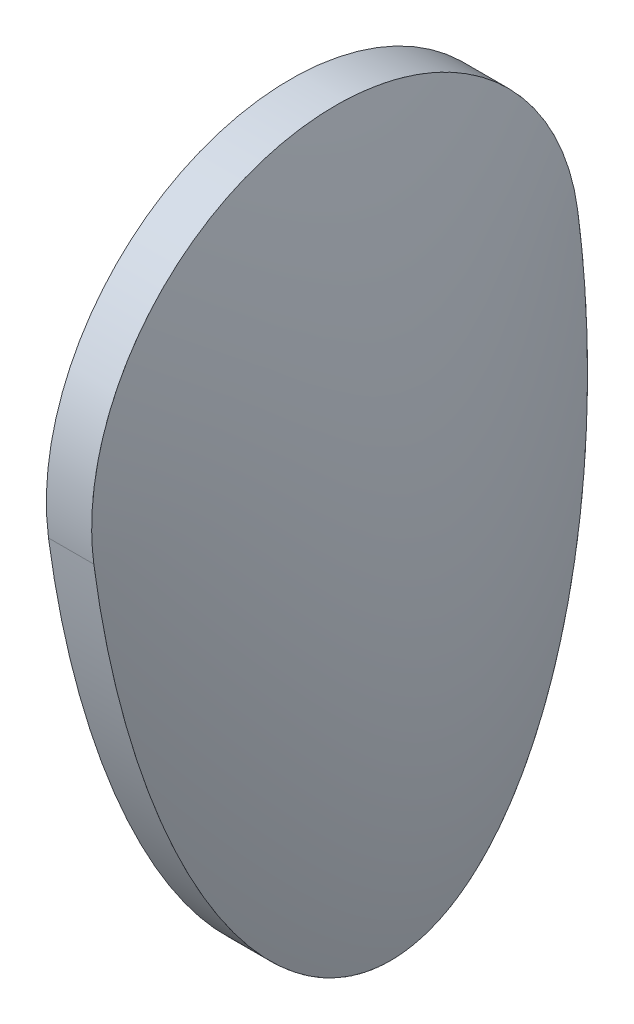
SolidWorks part; units mm, degrees
ref_plane "Plano frontal" through (0, 0, 0) normal (0, 0, 1) x (1, 0, 0)
ref_plane "Plano superior" through (0, 0, 0) normal (0, 1, 0) x (1, 0, 0)
ref_plane "Plano direito" through (0, 0, 0) normal (1, 0, 0) x (0, 0, -1)
sketch "Esboço43" plane through (0, 0, 0) normal (1, 0, 0) x (0, 0, -1)
  line L0 (0, 0) -> (0, -150) construction
  line L1 (0, -150) -> (20, -150) construction
  arc A0 (69.386, 9.2515) -> (-69.386, -9.2515) centre (0, 0) ccw
  ellipse E0 centre (0, 0) end of major axis (20, -150) minor radius 70 (-69.386, -9.2515) -> (69.386, 9.2515) ccw
  dimension "D1" = 140
  dimension "D2" = 150
  dimension "D3" = 20
extrude "Ressalto-extrusão11" add sketch "Esboço43" along normal blind 13
sketch3d "3DSketch4"
  arc A0 (13, 69.3586, 9.4543) -> (13, -149.9687, -20.2284) centre (-399.0364, -36.5209, -33.3487) cw
  arc A1 (13, 9.2515, -69.386) -> (13, -9.2515, 69.386) centre (13, 0, 0) ccw construction
  spline S0 degree 3 poles (13, -9.2515, 69.386) (13, -309.2515, 29.386) (13, -290.7485, -109.386) (13, 9.2515, -69.386) knots 0 0 0 0 1 1 1 1 weights 1 0.333333 0.333333 1 construction
  point P2 (-369.8245, 20.6877, -456.0665)
  point P8 (83, 0, 0)
surface "Superfície-Preenchimento3"
sketch "Esboço44" plane through (0, 0, 0) normal (1, 0, 0) x (0, 0, -1)
  line L0 (0, 70) -> (-25.8959, 70) construction
  circle A2 centre (-5, 28) radius 20
  spline S0 degree 3 poles (69.386, 9.2515) (69.3402, 9.5842) (69.2487, 10.2496) (69.0931, 11.2451) (68.9244, 12.2383) (68.741, 13.229) (68.5435, 14.217) (68.2109, 15.7648) (67.7009, 17.863) (66.9516, 20.4934) (65.8165, 23.9584) (64.1451, 28.2026) (62.1475, 32.3034) (59.9151, 36.2766) (56.9602, 40.8822) (53.5638, 45.1853) (49.234, 49.868) (45.2095, 53.5903) (40.8489, 56.8962) (37.0624, 59.4323) (33.1303, 61.7444) (29.0296, 63.7424) (24.8229, 65.4953) (20.5169, 67.0003) (16.1064, 68.1645) (11.6395, 69.0676) (7.1232, 69.7083) (2.5707, 69.9943) (-1.9867, 70.0133) (-7.4506, 69.7159) (-12.869, 68.8853) (-18.1923, 67.6377) (-22.565, 66.3386) (-26.8228, 64.7021) (-30.9737, 62.8208) (-35.011, 60.6977) (-38.8702, 58.266) (-42.5771, 55.6148) (-46.1256, 52.7486) (-49.4394, 49.6141) (-52.5613, 46.2939) (-56.0701, 42.0947) (-59.1579, 37.5653) (-61.8756, 32.821) (-64.3133, 27.9217) (-66.2647, 22.799) (-67.8063, 17.5533) (-68.8342, 13.109) (-69.5118, 8.5982) (-69.8414, 4.9669) (-69.9821, 2.2356) (-70.016, -0.4992) (-69.9434, -3.2333) (-69.7863, -5.6034) (-69.5935, -7.6093) (-69.4551, -8.7041) (-69.386, -9.2515) knots 0 0 0 0 0.004582 0.009165 0.013748 0.01833 0.022913 0.027495 0.039932 0.052369 0.064806 0.089675 0.114544 0.126981 0.15185 0.189142 0.201578 0.238871 0.263739 0.276177 0.301046 0.325914 0.338352 0.363221 0.38809 0.400527 0.425396 0.450265 0.462702 0.487571 0.524862 0.537299 0.562169 0.587037 0.599474 0.624344 0.649212 0.661649 0.686519 0.711387 0.723824 0.748694 0.785985 0.798423 0.823291 0.860583 0.87302 0.897889 0.922759 0.935195 0.947632 0.960069 0.972506 0.984943 0.992472 1 1 1 1 construction
  dimension "D1" = 40
  dimension "D3" = 42
  dimension "D2" = 5
  dimension "D4" = 70
extrude "Ressalto-extrusão12" add sketch "Esboço44" against normal blind 10
